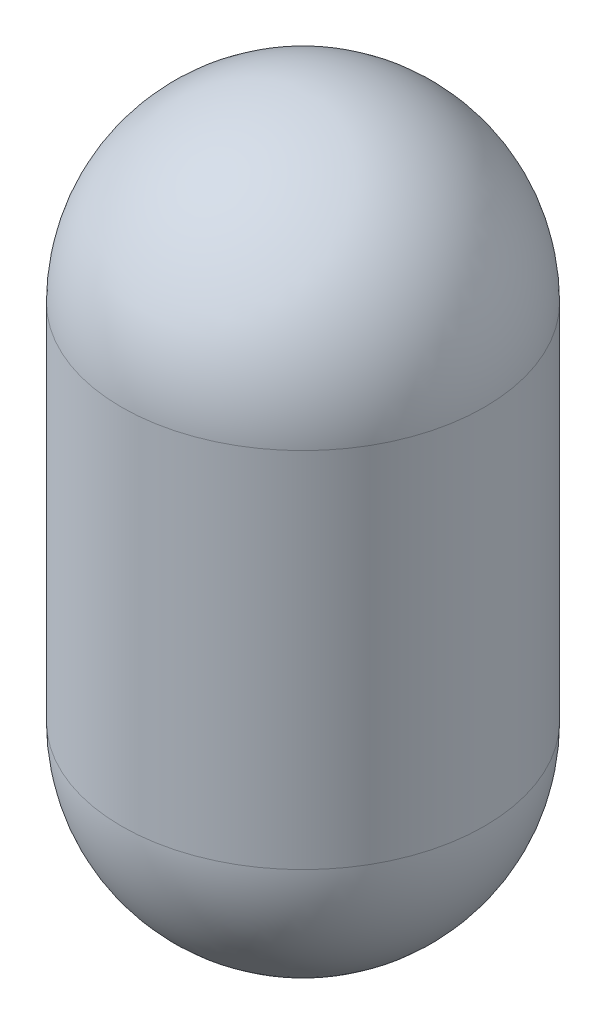
SolidWorks part; units mm, degrees
ref_plane "Front Plane" through (0, 0, 0) normal (0, 0, 1) x (1, 0, 0)
ref_plane "Top Plane" through (0, 0, 0) normal (0, 1, 0) x (1, 0, 0)
ref_plane "Right Plane" through (0, 0, 0) normal (1, 0, 0) x (0, 0, -1)
sketch "Sketch1" plane through (0, 0, 0) normal (0, 1, 0) x (1, 0, 0)
  circle A0 centre (0, 0) radius 9.5
extrude "Boss-Extrude1" add sketch "Sketch1" along normal blind 38
fillet "Fillet1" radius 9.5 2 edges at (0, 0, 9.5) (0, 38, 9.5)
